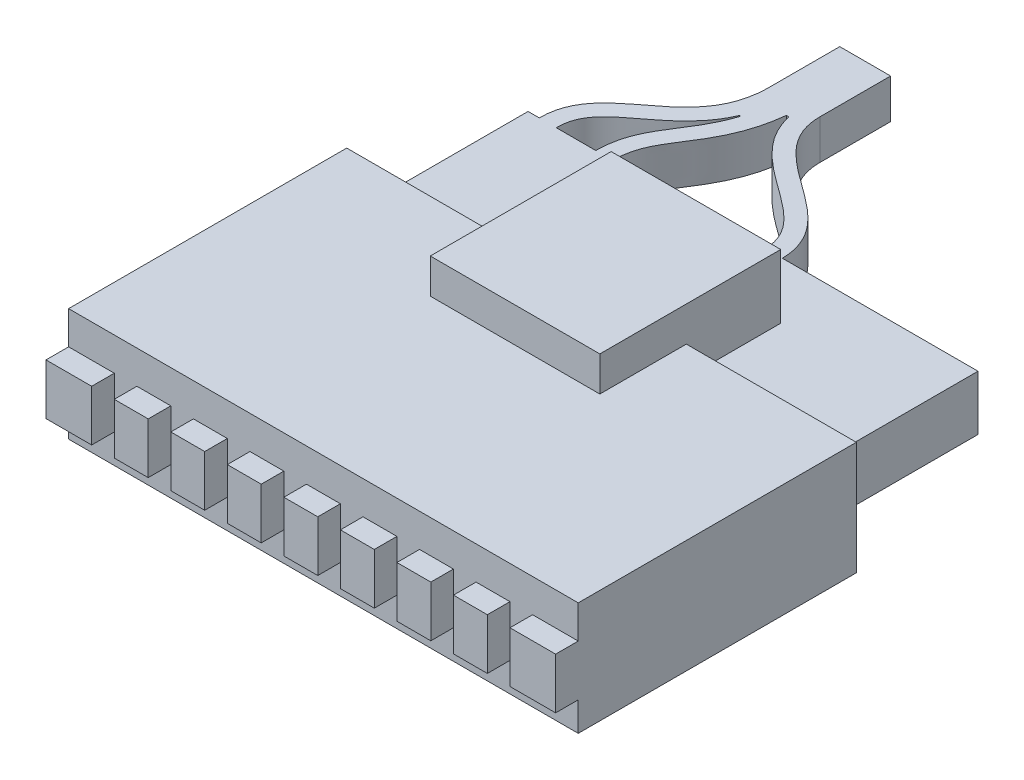
SolidWorks part; units mm, degrees
ref_plane "Front Plane" through (0, 0, 0) normal (0, 0, 1) x (1, 0, 0)
ref_plane "Top Plane" through (0, 0, 0) normal (0, 1, 0) x (1, 0, 0)
ref_plane "Right Plane" through (0, 0, 0) normal (1, 0, 0) x (0, 0, -1)
sketch "Sketch1" plane through (0, 0, 0) normal (0, 1, 0) x (1, 0, 0)
  line L1 (0, 0) -> (22.9, 0)
  line L2 (0, 0) -> (0, 12.4968)
  line L3 (0, 12.4968) -> (22.9, 12.4968)
  line L4 (22.9, 0) -> (22.9, 12.4968)
  dimension "D1" = 22.9
  dimension "D2" = 12.4968
extrude "Boss-Extrude1" add sketch "Sketch1" along normal blind 5.08
sketch "Sketch2" plane through (0, 0, 0) normal (0, 0, 1) x (1, 0, 0)
  line L0 (0, 5.08) -> (0, 0) construction
  line L1 (0, 3.5924) -> (22.9, 3.5924)
  line L2 (0, 3.5924) -> (0, 1.3064)
  line L3 (0, 1.3064) -> (22.9, 1.3064)
  line L4 (22.9, 3.5924) -> (22.9, 1.3064)
  line L5 (22.9, 5.08) -> (22.9, 0) construction
  dimension "D1" = 2.286
extrude "Boss-Extrude2" add sketch "Sketch2" along normal blind 1.016
sketch "Sketch3" plane through (0, 5.08, 0) normal (0, 1, 0) x (1, 0, 0)
  line L0 (2.052, -1.016) -> (2.052, 0)
  line L1 (3.068, -1.016) -> (3.068, 0)
  line L2 (2.052, 0) -> (3.068, 0)
  line L3 (2.052, -1.016) -> (3.068, -1.016)
  line L4 (22.9, 0) -> (0, 0)
  line L5 (0, 0) -> (0, -1.016)
  line L6 (0, -1.016) -> (22.9, -1.016)
  line L7 (22.9, -1.016) -> (22.9, 0)
  line L8 (22.9, 0) -> (0, 0) construction
  line L9 (0, 0) -> (0, -1.016) construction
  line L10 (0, -1.016) -> (22.9, -1.016) construction
  line L11 (22.9, -1.016) -> (22.9, 0) construction
  line L12 (4.592, -1.016) -> (4.592, 0)
  line L13 (5.608, -1.016) -> (5.608, 0)
  line L14 (4.592, 0) -> (5.608, 0)
  line L15 (4.592, -1.016) -> (5.608, -1.016)
  line L16 (7.132, -1.016) -> (7.132, 0)
  line L17 (8.148, -1.016) -> (8.148, 0)
  line L18 (7.132, 0) -> (8.148, 0)
  line L19 (7.132, -1.016) -> (8.148, -1.016)
  line L20 (9.672, -1.016) -> (9.672, 0)
  line L21 (10.688, -1.016) -> (10.688, 0)
  line L22 (9.672, 0) -> (10.688, 0)
  line L23 (9.672, -1.016) -> (10.688, -1.016)
  line L24 (12.212, -1.016) -> (12.212, 0)
  line L25 (13.228, -1.016) -> (13.228, 0)
  line L26 (12.212, 0) -> (13.228, 0)
  line L27 (12.212, -1.016) -> (13.228, -1.016)
  line L28 (14.752, -1.016) -> (14.752, 0)
  line L29 (15.768, -1.016) -> (15.768, 0)
  line L30 (14.752, 0) -> (15.768, 0)
  line L31 (14.752, -1.016) -> (15.768, -1.016)
  line L32 (17.292, -1.016) -> (17.292, 0)
  line L33 (18.308, -1.016) -> (18.308, 0)
  line L34 (17.292, 0) -> (18.308, 0)
  line L35 (17.292, -1.016) -> (18.308, -1.016)
  line L36 (19.832, -1.016) -> (19.832, 0)
  line L37 (20.848, -1.016) -> (20.848, 0)
  line L38 (19.832, 0) -> (20.848, 0)
  line L39 (19.832, -1.016) -> (20.848, -1.016)
  line L40 (2.052, -1.016) -> (4.592, -1.016) construction
  line L41 (11.45, 0) -> (11.45, -1.016) construction
  line L42 (10.688, 0) -> (11.45, -1.016) construction
  line L43 (11.45, -1.016) -> (12.212, 0) construction
  dimension "D3" = 2.54
  dimension "D4" = 1.016
  dimension "D1" = 0
  dimension "D2" = 8
extrude "Cut-Extrude1" cut sketch "Sketch3" against normal through all
sketch "Sketch4" plane through (0, 0, -12.4968) normal (0, 0, -1) x (-1, 0, 0)
  line L0 (-22.9, 2.54) -> (0, 2.54) construction
  line L1 (-11.45, 5.08) -> (-11.45, 0) construction
  line L2 (-21.5592, 3.7719) -> (-1.3408, 3.7719)
  line L3 (-21.5592, 3.7719) -> (-21.5592, 1.3081)
  line L4 (-22.9, 0) -> (0, 0)
  line L5 (0, 0) -> (0, 5.08)
  line L6 (0, 5.08) -> (-22.9, 5.08)
  line L7 (-22.9, 5.08) -> (-22.9, 0)
  line L8 (-22.9, 0) -> (0, 0) construction
  line L9 (0, 0) -> (0, 5.08) construction
  line L10 (0, 5.08) -> (-22.9, 5.08) construction
  line L11 (-22.9, 5.08) -> (-22.9, 0) construction
  line L12 (-21.5592, 1.3081) -> (-1.3408, 1.3081)
  line L13 (-1.3408, 3.7719) -> (-1.3408, 1.3081)
  point P12 (-21.5592, 2.54)
  point P13 (-11.45, 3.7719)
  dimension "D2" = 20.2184
  dimension "D3" = 2.4638
  dimension "D1" = 0
extrude "Boss-Extrude3" add sketch "Sketch4" along normal blind 6.8072
sketch "Sketch5" plane through (0, 3.7719, 0) normal (0, 1, 0) x (1, 0, 0)
  line L0 (11.45, 19.304) -> (11.45, -49980.696) construction
  line L2 (15.26, 8.6106) -> (7.64, 8.6106)
  line L3 (15.26, 8.6106) -> (15.26, 16.7386)
  line L4 (1.3408, 12.4968) -> (21.5592, 12.4968)
  line L5 (21.5592, 12.4968) -> (21.5592, 19.304)
  line L6 (21.5592, 19.304) -> (1.3408, 19.304)
  line L7 (1.3408, 19.304) -> (1.3408, 12.4968)
  line L8 (1.3408, 12.4968) -> (21.5592, 12.4968) construction
  line L9 (21.5592, 12.4968) -> (21.5592, 19.304) construction
  line L10 (21.5592, 19.304) -> (1.3408, 19.304) construction
  line L11 (1.3408, 19.304) -> (1.3408, 12.4968) construction
  line L12 (15.26, 16.7386) -> (7.64, 16.7386)
  line L13 (7.64, 8.6106) -> (7.64, 16.7386)
  point P6 (11.45, 19.304)
  point P11 (11.45, 8.6106)
  dimension "D2" = 7.62
  dimension "D3" = 8.128
  dimension "D4" = 4.2418
  dimension "D1" = 0
extrude "Boss-Extrude4" add sketch "Sketch5" along normal blind 2.8702
sketch "Sketch6" plane through (0, 3.7719, 0) normal (0, 1, 0) x (1, 0, 0)
  line L0 (1.3408, 19.304) -> (21.5592, 19.304) construction
  line L1 (8.1076, 25.654) -> (8.1076, 28.829)
  line L2 (8.1076, 28.829) -> (5.8218, 28.829)
  line L3 (5.8218, 28.829) -> (5.8218, 25.6727)
  line L4 (12.7648, 19.304) -> (12.0028, 19.304)
  line L5 (5.8218, 28.6646) -> (5.8218, 22.8776) construction
  line L6 (4.3828, 21.336) -> (4.3828, 17.272) construction
  line L7 (5.1448, 19.304) -> (4.3828, 19.304)
  line L8 (15.26, 16.7386) -> (15.26, 12.4968)
  line L9 (15.26, 12.4968) -> (21.5592, 12.4968)
  line L10 (21.5592, 12.4968) -> (21.5592, 19.304)
  line L11 (21.5592, 19.304) -> (1.3408, 19.304)
  line L12 (1.3408, 19.304) -> (1.3408, 12.4968)
  line L13 (1.3408, 12.4968) -> (7.64, 12.4968)
  line L14 (7.64, 12.4968) -> (7.64, 16.7386)
  line L15 (7.64, 16.7386) -> (15.26, 16.7386)
  line L16 (15.26, 16.7386) -> (15.26, 12.4968) construction
  line L17 (15.26, 12.4968) -> (21.5592, 12.4968) construction
  line L18 (21.5592, 12.4968) -> (21.5592, 19.304) construction
  line L19 (21.5592, 19.304) -> (1.3408, 19.304) construction
  line L20 (1.3408, 19.304) -> (1.3408, 12.4968) construction
  line L21 (1.3408, 12.4968) -> (7.64, 12.4968) construction
  line L22 (7.64, 12.4968) -> (7.64, 16.7386) construction
  line L23 (7.64, 16.7386) -> (15.26, 16.7386) construction
  line L24 (1.8428, 21.7136) -> (1.8428, 16.8944) construction
  line L25 (2.6048, 19.304) -> (1.8428, 19.304)
  line L26 (12.0028, 21.2944) -> (12.0028, 17.3136) construction
  line L27 (5.8218, 28.703) -> (5.8218, 22.9159) construction
  line L28 (7.3456, 28.3628) -> (7.3456, 22.9358) construction
  line L32 (7.4173, 24.952) -> (7.299, 24.952)
  line L33 (6.3007, 23.8803) -> (6.2508, 23.9086)
  spline S0 degree 3 poles (1.8428, 19.304) (1.8428, 22.316) (5.8218, 22.0558) (5.8218, 25.6727) knots 0 0 0 0 1 1 1 1
  spline S1 degree 1 poles (2.6048, 19.304) (6.5838, 25.6727) knots 0 0 1 1 construction
  spline S2 degree 3 poles (2.6048, 19.304) (2.6048, 19.4362) (2.6288, 19.7174) (2.7488, 20.134) (3.017, 20.5812) (3.5619, 21.1016) (4.2832, 21.6428) (5.0831, 22.2696) (5.7505, 22.9758) (6.1327, 23.6244) (6.2983, 24.0192) (6.4281, 24.3954) (6.5478, 24.9096) (6.5838, 25.4235) (6.5838, 25.6727) knots 0 0 0 0 0.0625 0.125 0.25 0.375 0.5 0.625 0.75 0.824094 0.855344 0.875 0.9375 1 1 1 1
  spline S3 degree 3 poles (4.3828, 19.304) (4.3828, 21.844) (6.5006, 22.2811) (6.5838, 25.6727) knots 0 0 0 0 1 1 1 1
  spline S4 degree 1 poles (5.1448, 19.304) (7.3456, 25.654) knots 0 0 1 1 construction
  spline S5 degree 3 poles (5.1448, 19.304) (5.1448, 19.4278) (5.1586, 19.6859) (5.2313, 20.1137) (5.3941, 20.5878) (5.6955, 21.1405) (6.0882, 21.7439) (6.5247, 22.448) (6.9351, 23.3026) (7.1745, 24.123) (7.2776, 24.7546) (7.3242, 25.173) (7.3412, 25.4744) (7.3456, 25.654) knots 0 0 0 0 0.0625 0.125 0.25 0.375 0.5 0.625 0.75 0.875 0.918103 0.949353 1 1 1 1
  spline S6 degree 3 poles (12.0028, 19.304) (12.0028, 21.792) (7.3456, 22.2622) (7.3456, 25.654) knots 0 0 0 0 1 1 1 1
  spline S7 degree 1 poles (12.7648, 19.304) (8.1076, 25.654) knots 0 0 1 1 construction
  spline S8 degree 3 poles (12.7648, 19.304) (12.7648, 19.5132) (12.7138, 19.9404) (12.4305, 20.69) (11.8437, 21.4345) (10.9987, 22.1289) (10.1141, 22.7551) (9.291, 23.3798) (8.6341, 24.0399) (8.287, 24.6371) (8.1363, 25.1704) (8.1076, 25.4972) (8.1076, 25.654) knots 0 0 0 0 0.0625 0.125 0.25 0.375 0.5 0.625 0.75 0.875 0.9375 1 1 1 1
  line M12 (21.5592, 19.304) -> (1.3408, 19.304)
  dimension "D4" = 2.54
  dimension "D6" = 7.62
  dimension "D7" = 6.35
  dimension "D8" = 9.525
  dimension "D1" = 0
  dimension "D2" = 0.762
  dimension "D3" = 0.762
  dimension "D5" = 0.762
extrude "Boss-Extrude6" add sketch "Sketch6" against normal blind 1.778 contours S8 L1 L2 L3 S0 S2 S3 S5 S6 M12 | L32 S6 S5 | L33 S3 S2 | S3 S2
